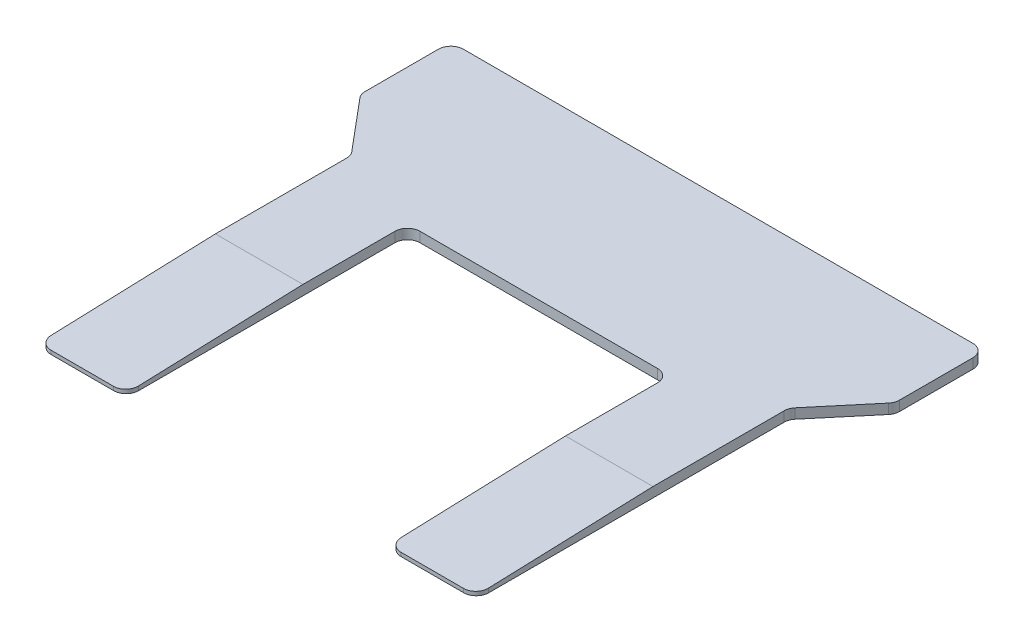
SolidWorks part; units mm, degrees
ref_plane "Front Plane" through (0, 0, 0) normal (0, 0, 1) x (1, 0, 0)
ref_plane "Top Plane" through (0, 0, 0) normal (0, 1, 0) x (1, 0, 0)
ref_plane "Right Plane" through (0, 0, 0) normal (1, 0, 0) x (0, 0, -1)
sketch "Sketch1" plane through (0, 0, 0) normal (0, 1, 0) x (1, 0, 0)
  line L0 (-35, -24.4279) -> (-35, -71.7)
  line L9 (-35.4679, -23.1424) -> (-42.2821, -15.0215)
  line L10 (-42.75, -13.736) -> (-42.75, -2)
  line L13 (42.75, -2) -> (42.75, -13.736)
  line L14 (42.2821, -15.0215) -> (35.4679, -23.1424)
  line L16 (-40.75, 0) -> (40.75, 0)
  line L17 (-33, -73.7) -> (-23, -73.7)
  line L18 (35, -71.7) -> (35, -24.4279)
  line L19 (-21, -71.7) -> (-21, -30.7)
  line L20 (-19, -28.7) -> (19, -28.7)
  line L21 (21, -30.7) -> (21, -71.7)
  line L22 (23, -73.7) -> (33, -73.7)
  line L23 (-42.75, -12.7) -> (42.75, -12.7) construction
  arc A8 (-21, -30.7) -> (-19, -28.7) centre (-19, -30.7) cw
  arc A9 (19, -28.7) -> (21, -30.7) centre (19, -30.7) cw
  arc A10 (33, -73.7) -> (35, -71.7) centre (33, -71.7) ccw
  arc A11 (21, -71.7) -> (23, -73.7) centre (23, -71.7) ccw
  arc A12 (-21, -71.7) -> (-23, -73.7) centre (-23, -71.7) cw
  arc A13 (-35, -71.7) -> (-33, -73.7) centre (-33, -71.7) ccw
  arc A16 (35.4679, -23.1424) -> (35, -24.4279) centre (37, -24.4279) ccw
  arc A17 (42.75, -13.736) -> (42.2821, -15.0215) centre (40.75, -13.736) cw
  arc A18 (40.75, 0) -> (42.75, -2) centre (40.75, -2) cw
  arc A19 (-42.75, -2) -> (-40.75, 0) centre (-40.75, -2) cw
  arc A20 (-42.2821, -15.0215) -> (-42.75, -13.736) centre (-40.75, -13.736) cw
  arc A21 (-35.4679, -23.1424) -> (-35, -24.4279) centre (-37, -24.4279) cw
  point P8 (-21, -28.7)
  point P14 (35, 0)
  point P16 (21, -73.7)
  point P17 (-35, 0)
  point P20 (-21, -73.7)
  point P23 (-35, -73.7)
  point P34 (35, -23.7)
  point P39 (42.75, -14.4639)
  point P47 (42.75, 0)
  point P50 (-42.75, 0)
  point P53 (-42.75, -14.4639)
  point P56 (-35, -23.7)
  dimension "D7" = 50
  dimension "D8" = 140
  dimension "D9" = 2
  dimension "D15" = 2
  dimension "D1" = 73.7
  dimension "D2" = 42
  dimension "D3" = 85.5
  dimension "D4" = 45
  dimension "D5" = 14
  dimension "D6" = 70
  dimension "D10" = 12.7
extrude "Boss-Extrude1" add sketch "Sketch1" along normal blind 1.5875
ref_plane "Plane1" through (37, 0, 0) normal (1, 0, 0) x (0, 0, -1)
sketch "Sketch3" plane through (37, 0, 0) normal (1, 0, 0) x (0, 0, -1)
  line L0 (-71.7, 1.5875) -> (-24.4279, 1.5875) construction
  line L1 (-71.7, 1.5875) -> (-73.7, 1.5875) construction
  line L2 (-73.7, 1.5875) -> (-73.7, 0) construction
  line L3 (-71.7, 1.5875) -> (-45.4217, 1.5875)
  line L4 (-71.7, 1.5875) -> (-73.7, 1.5875)
  line L5 (-73.7, 1.5875) -> (-73.7, 0.6)
  line L6 (-73.7, 0.6) -> (-45.4217, 1.5875)
  line L7 (-73.7, 0) -> (-71.7, 0) construction
  dimension "D1" = 2
  dimension "D2" = 0.6
extrude "Cut-Extrude2" cut sketch "Sketch3" against normal through all
